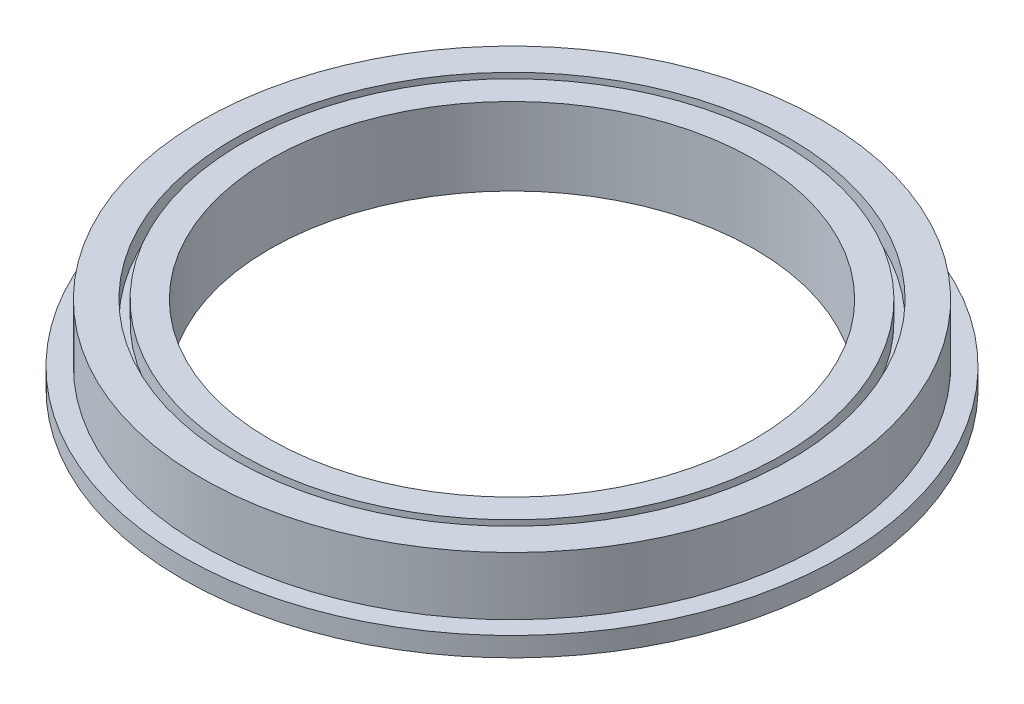
SolidWorks part; units mm, degrees
material "合金钢"
ref_plane "前视基准面" through (0, 0, 0) normal (0, 0, 1) x (1, 0, 0)
ref_plane "上视基准面" through (0, 0, 0) normal (0, 1, 0) x (1, 0, 0)
ref_plane "右视基准面" through (0, 0, 0) normal (1, 0, 0) x (0, 0, -1)
sketch "草图1" plane through (0, 0, 0) normal (0, 0, 1) x (1, 0, 0)
  line L0 (0, 0) -> (0, 9.7564) construction
  line L1 (12.5, 3) -> (12.5, 0)
  line L2 (12.5, 0) -> (16, 0)
  line L3 (16, 0) -> (16, 3)
  line L4 (16, 3) -> (12.5, 3)
  dimension "D1" = 25
  dimension "D2" = 32
  dimension "D3" = 3
revolve "旋转1" add sketch "草图1" angle 360 about L0
sketch "草图2" plane through (0, 0, 0) normal (0, -1, 0) x (1, 0, 0)
  circle A0 centre (0, 0) radius 17
  circle A1 centre (0, 0) radius 12.5
  dimension "D1" = 34
  dimension "D2" = 25
extrude "凸台-拉伸1" add sketch "草图2" along normal blind 1
sketch "草图3" plane through (0, 3, 0) normal (0, 1, 0) x (1, 0, 0)
  circle A0 centre (0, 0) radius 14.3404
  circle A1 centre (0, 0) radius 13.9323
extrude "切除-拉伸1" cut sketch "草图3" against normal blind 1
